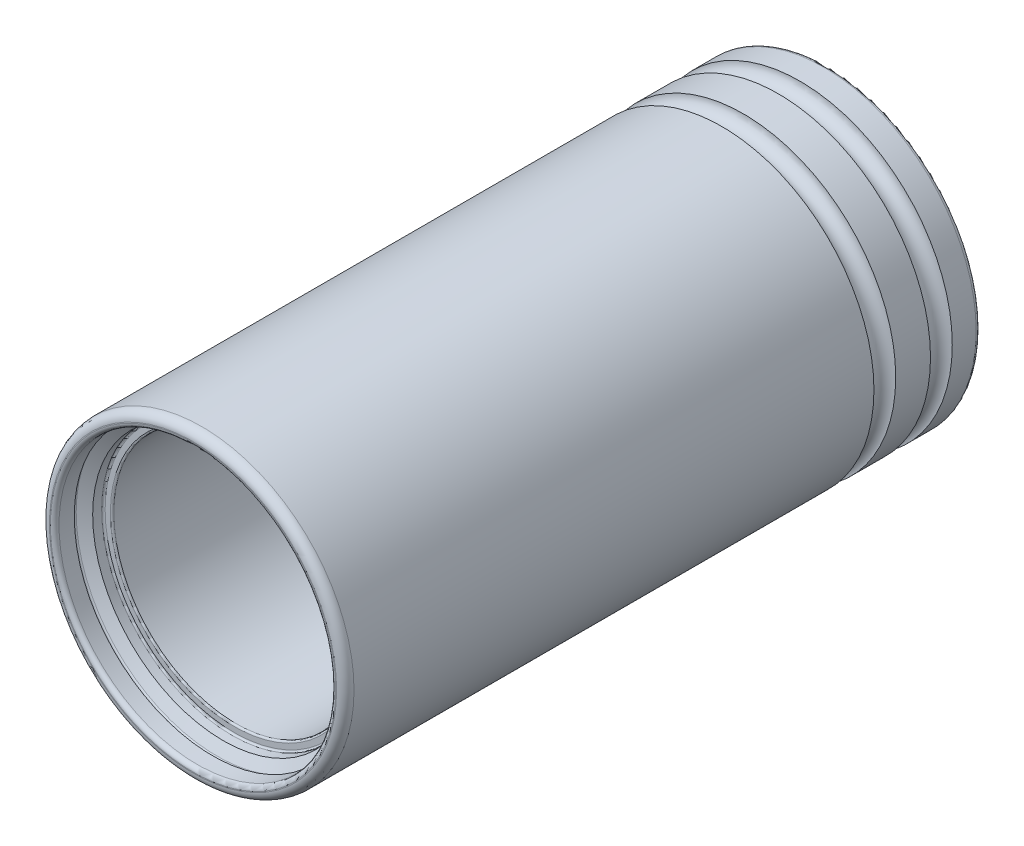
SolidWorks part; units mm, degrees
material "AISI 304"
ref_plane "Спереди" through (0, 0, 0) normal (0, 0, 1) x (1, 0, 0)
ref_plane "Сверху" through (0, 0, 0) normal (0, 1, 0) x (1, 0, 0)
ref_plane "Справа" through (0, 0, 0) normal (1, 0, 0) x (0, 0, -1)
sketch "Эскиз1" plane through (0, 0, 0) normal (0, 0, 1) x (1, 0, 0)
  circle A0 centre (0, 0) radius 17.5
  dimension "D1" = 35
extrude "Бобышка-Вытянуть1" add sketch "Эскиз1" against normal blind 73
sketch "Эскиз4" plane through (0, 0, 0) normal (1, 0, 0) x (0, 0, -1)
  line L0 (0, 0) -> (0, 15)
  line L1 (0, 17.5) -> (0, -17.5) construction
  line L2 (0, 15) -> (4.7, 15)
  line L3 (4.7, 15) -> (4.7, 14)
  line L4 (4.7, 14) -> (23.3, 14)
  line L5 (23.3, 14) -> (23.3, 11)
  line L6 (23.3, 11) -> (29.1001, 9.5)
  line L7 (29.1001, 9.5) -> (30.8, 9.5)
  line L8 (30.8, 9.5) -> (30.8, 10.1)
  line L9 (30.8, 10.1) -> (32, 10.1)
  line L10 (32, 10.1) -> (32.3464, 9.5)
  line L11 (32.3464, 9.5) -> (46, 9.5)
  line L12 (46, 9.5) -> (46, 7.5)
  line L13 (46, 7.5) -> (46.5236, 5.5)
  line L14 (46.5236, 5.5) -> (50, 5.5)
  line L15 (50, 5.5) -> (50, 9.5)
  line L16 (50, 9.5) -> (53.8, 9.5)
  line L20 (55, 9.5) -> (56.5, 9.5)
  line L21 (56.5, 9.5) -> (56.5, 10.75)
  line L22 (56.5, 10.75) -> (68, 10.75)
  line L23 (68, 10.75) -> (68, 12.4)
  line L24 (68, 12.4) -> (71, 12.4)
  line L25 (71, 12.4) -> (71, 10.75)
  line L26 (71, 10.75) -> (73, 10.75)
  line L27 (73, -17.5) -> (73, 17.5) construction
  line L28 (73, 10.75) -> (73, 0)
  line L29 (73, 0) -> (0, 0)
  arc A0 (53.8, 9.5) -> (55, 9.5) centre (54.4, 9.5) cw
  dimension "D8" = 0.6
  dimension "D1" = 10.75
  dimension "D2" = 12.4
  dimension "D3" = 2
  dimension "D4" = 3
  dimension "D5" = 16.5
  dimension "D6" = 2.1
  dimension "D7" = 9.5
  dimension "D10" = 75.329
  dimension "D11" = 14.5
  dimension "D12" = 15
  dimension "D13" = 14
  dimension "D14" = 4.7
  dimension "D15" = 23.3
  dimension "D16" = 60
  dimension "D17" = 11
  dimension "D18" = 5.5
  dimension "D19" = 1.2
  dimension "D20" = 23
  dimension "D21" = 30.8
  dimension "D22" = 46
  dimension "D23" = 7.5
revolve "Вырез-Повернуть1" cut sketch "Эскиз4" angle 360 about L29
sketch "Эскиз5" plane through (0, 0, 0) normal (1, 0, 0) x (0, 0, -1)
  line L0 (3.466, 15) -> (1.734, 15)
  line L1 (1.734, 15) -> (2.6, 16.5)
  line L2 (2.6, 16.5) -> (3.466, 15)
  line L3 (4.7, 15) -> (4.7, -15) construction
  line L4 (4.7, 15) -> (4.7, -15) construction
  line L5 (0, 15) -> (0, -15) construction
  line L6 (0, 0) -> (8.2655, 0) construction
  line L7 (0, 17.5) -> (0, -17.5) construction
  line L8 (0, 17.5) -> (0, -17.5) construction
  point P3 (2.6, 15)
  dimension "D1" = 1
  dimension "D2" = 60
  dimension "D3" = 2.6
revolve "Вырез-Повернуть2" cut sketch "Эскиз5" angle 360 about L6
fillet "Скругление1" radius 0.2 2 edges at (16.5, 0, -2.6) (-15, 0, -4.7)
fillet "Скругление2" radius 1 2 edges at (-14, 0, -23.3) (17.5, 0, 0)
sketch "Эскиз6" plane through (0, 0, 0) normal (0, 0, 1) x (1, 0, 0)
  circle A0 centre (0, 0) radius 14 construction
  circle A1 centre (0, 0) radius 14
  circle A2 centre (0, 0) radius 15.9
  dimension "D1" = 31.8
extrude "Вырез-Вытянуть1" cut sketch "Эскиз6" against normal blind 2.6
fillet "Скругление3" radius 0.5 6 edges at (-10.75, 0, -73) (17.5, 0, -73) (-5.5, 0, -50) (-5.5, 0, -46.5236) (-9.5, 0, -29.1001) (-11, 0, -23.3)
fillet "Скругление4" radius 0.1 2 edges at (-10.1, 0, -32) (-10.1, 0, -30.8)
fillet "Скругление5" radius 0.2 4 edges at (-10.75, 0, -71) (-10.75, 0, -68) (-9.5, 0, -32.3464) (-9.5, 0, -30.8)
fillet "Скругление6" radius 0.4 2 edges at (-12.4, 0, -71) (-12.4, 0, -68)
fillet "Скругление7" radius 0.2 3 edges at (-10.75, 0, -56.5) (-9.5, 0, -56.5) (-14, 0, -4.7)
sketch "Эскиз7" plane through (0, 0, 0) normal (0, 1, 0) x (1, 0, 0)
  line L0 (17, 73) -> (-17, 73) construction
  line L1 (-15.75, 73) -> (-13.25, 73)
  line L2 (0, 88.9589) -> (0, 57.4428) construction
  arc A0 (-15.75, 73) -> (-13.25, 73) centre (-14.5, 73) cw
  dimension "D1" = 1.25
  dimension "D2" = 14.5
revolve "Повернуть1" add sketch "Эскиз7" angle 360 about L2
sketch "Эскиз8" plane through (0, 0, 0) normal (1, 0, 0) x (0, 0, -1)
  line L0 (1, -17.5) -> (1, 17.5) construction
  line L1 (1, -17.5) -> (1, 17.5) construction
  line L2 (68.5, 17.5) -> (40.6285, 17.5) construction
  line L7 (0, 0) -> (74.6339, 0) construction
  line L8 (73, -17) -> (73, 17) construction
  line L9 (73, -17) -> (73, 17) construction
  line L10 (72.5, 17.5) -> (1, 17.5) construction
  circle A0 centre (68.5, 17.5) radius 1.25
  circle A1 centre (62, 17.5) radius 1.25
  dimension "D1" = 2.5
  dimension "D3" = 2.5
  dimension "D4" = 6.5
  dimension "D2" = 4.5
revolve "Вырез-Повернуть3" cut sketch "Эскиз8" angle 360 about L7
fillet "Скругление10" radius 0.2 1 edges at (-9.5, 0, -50)
fillet "Скругление11" radius 0.5 1 edges at (15.9, 0, 0)
